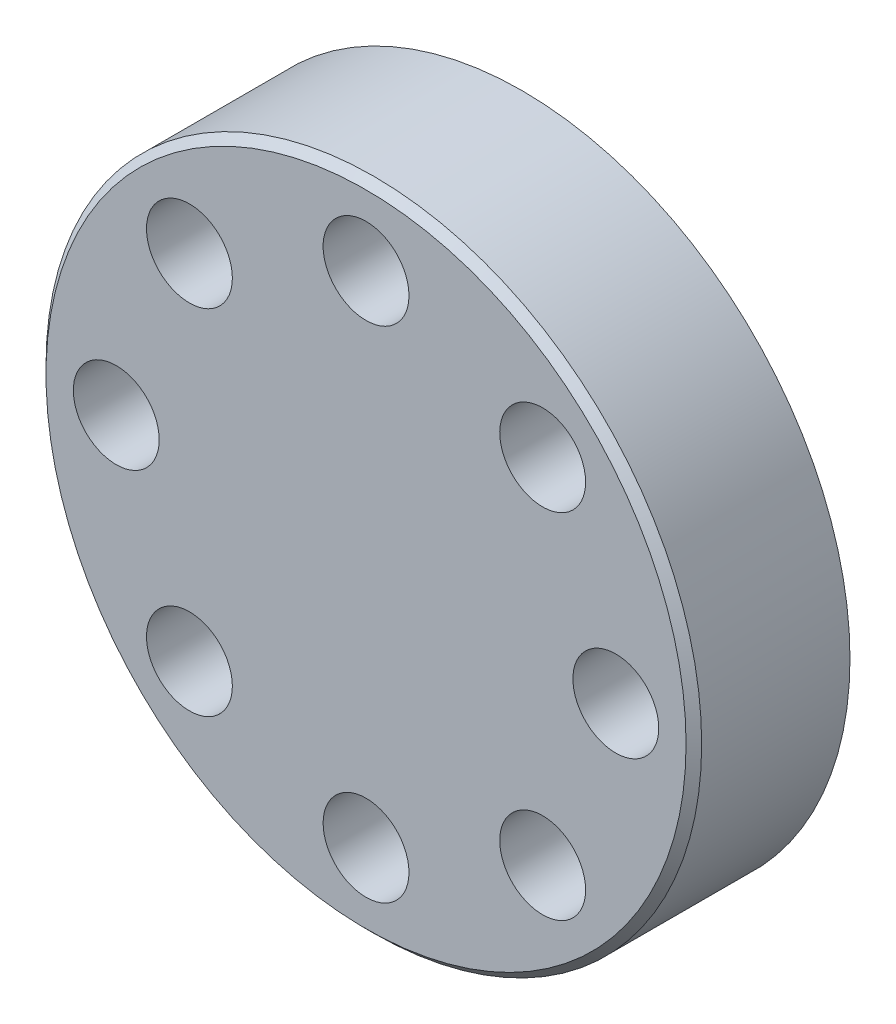
SolidWorks part; units mm, degrees
material "1.4000 (X6Cr13)"
ref_plane "Piano frontale" through (0, 0, 0) normal (0, 0, 1) x (1, 0, 0)
ref_plane "Piano superiore" through (0, 0, 0) normal (0, 1, 0) x (1, 0, 0)
ref_plane "Piano destro" through (0, 0, 0) normal (1, 0, 0) x (0, 0, -1)
sketch "Schizzo1" plane through (0, 0, 0) normal (0, 0, 1) x (1, 0, 0)
  circle A0 centre (0, 0) radius 7
  dimension "D1" = 14
extrude "Estrusione-Estrusione1" add sketch "Schizzo1" along normal blind 8
sketch "Schizzo2" plane through (0, 0, 8) normal (0, 0, 1) x (1, 0, 0)
  circle A0 centre (0, 0) radius 21
  dimension "D1" = 42
extrude "Estrusione-Estrusione2" add sketch "Schizzo2" along normal blind 10
sketch "Schizzo3" plane through (0, 0, 18) normal (0, 0, 1) x (1, 0, 0)
  circle A0 centre (0, 0) radius 16 construction
  circle A1 centre (0, 16) radius 2.75
  dimension "D1" = 32
  dimension "D2" = 5.5
extrude "Taglio-Estrusione1" cut sketch "Schizzo3" against normal through all
pattern_circular "RipetizioneCircolare1" count 8 over 360 about axis through (0, 0, 0) along (0, 0, 1) of "Taglio-Estrusione1"
chamfer "Smusso1" distance 0.5 angle 45 1 edges at (7, 0, 0)
chamfer "Smusso2" distance 0.5 angle 45 1 edges at (21, 0, 18)
